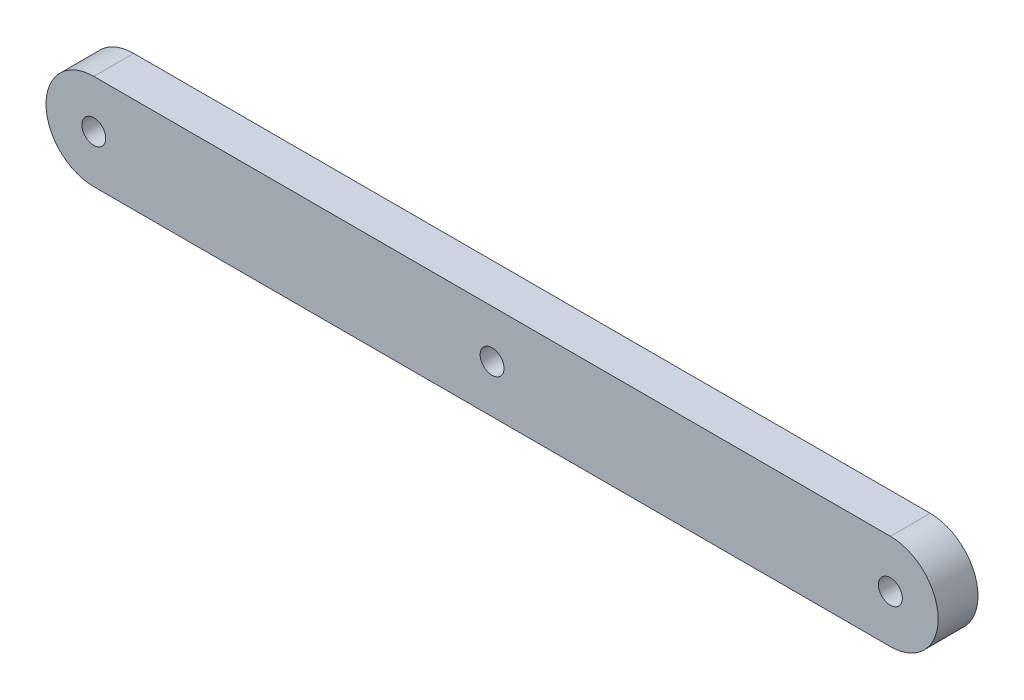
SolidWorks part; units mm, degrees
ref_plane "Plan de face" through (0, 0, 0) normal (0, 0, 1) x (1, 0, 0)
ref_plane "Plan de dessus" through (0, 0, 0) normal (0, 1, 0) x (1, 0, 0)
ref_plane "Plan de droite" through (0, 0, 0) normal (1, 0, 0) x (0, 0, -1)
sketch "Esquisse1" plane through (0, 0, 0) normal (0, 0, 1) x (1, 0, 0)
  line L0 (-50, 0) -> (50, 0) construction
  line L1 (-50, 6) -> (50, 6)
  line L2 (-50, -6) -> (50, -6)
  arc A0 (-50, 6) -> (-50, -6) centre (-50, 0) ccw
  arc A1 (50, -6) -> (50, 6) centre (50, 0) ccw
  circle A2 centre (-50, 0) radius 1.5
  circle A3 centre (50, 0) radius 1.5
  circle A4 centre (0, 0) radius 1.5
  point P2 (0, 0)
  dimension "D1" = 6
  dimension "D3" = 3
  dimension "D4" = 3
  dimension "D5" = 3
  dimension "D2" = 100
extrude "Boss.-Extru.1" add sketch "Esquisse1" along normal blind 5
